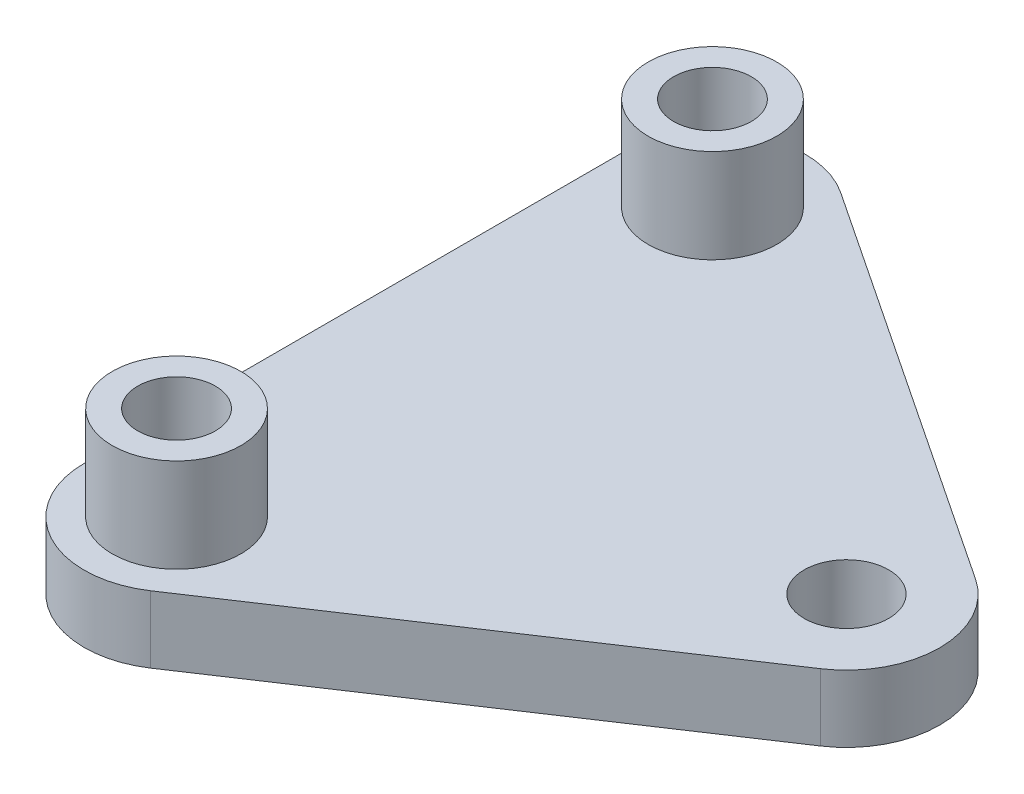
SolidWorks part; units mm, degrees
ref_plane "Alzado" through (0, 0, 0) normal (0, 0, 1) x (1, 0, 0)
ref_plane "Planta" through (0, 0, 0) normal (0, 1, 0) x (1, 0, 0)
ref_plane "Vista lateral" through (0, 0, 0) normal (1, 0, 0) x (0, 0, -1)
sketch "Croquis2" plane through (0, 0, 0) normal (0, 1, 0) x (1, 0, 0)
  line L0 (0, 0) -> (23.3569, 0) construction
  line L1 (-3.45, 10) -> (-3.45, -10)
  line L2 (1.9097, 12.8732) -> (16.9236, 2.894)
  line L3 (1.9097, -12.8732) -> (16.9236, -2.894)
  circle A0 centre (0, 10) radius 1.45
  circle A1 centre (0, -10) radius 1.45
  circle A2 centre (15, 0) radius 1.475 construction
  arc A3 (1.9097, 12.8732) -> (-3.45, 10) centre (0, 10) ccw
  arc A4 (1.9097, -12.8732) -> (-3.45, -10) centre (0, -10) cw
  arc A5 (16.9236, -2.894) -> (16.9236, 2.894) centre (15, 0) ccw
  circle A7 centre (0, 10) radius 3.45 construction
  circle A8 centre (0, -10) radius 3.45 construction
  circle A9 centre (15, 0) radius 3.475 construction
  point P10 (3.45, -10)
  point P12 (18.475, 0)
  point P21 (3.45, 10)
  dimension "D1" = 2.9
  dimension "D2" = 10
  dimension "D3" = 2.95
  dimension "D4" = 15
  dimension "D5" = 2
extrude "Saliente-Extruir1" add sketch "Croquis2" along normal blind 2.5
sketch "Croquis3" plane through (0, 2.5, 0) normal (0, 1, 0) x (1, 0, 0)
  circle A0 centre (0, 10) radius 2.4
  circle A1 centre (0, -10) radius 2.4
  circle A2 centre (0, 10) radius 1.45
  circle A3 centre (0, -10) radius 1.45
  dimension "D1" = 4.8
  dimension "D2" = 4.8
extrude "Saliente-Extruir2" add sketch "Croquis3" along normal blind 3.5
sketch "Croquis4" plane through (0, 2.5, 0) normal (0, 1, 0) x (1, 0, 0)
  circle A0 centre (15, 0) radius 1.575
  dimension "D1" = 3.15
extrude "Cortar-Extruir1" cut sketch "Croquis4" against normal through all
